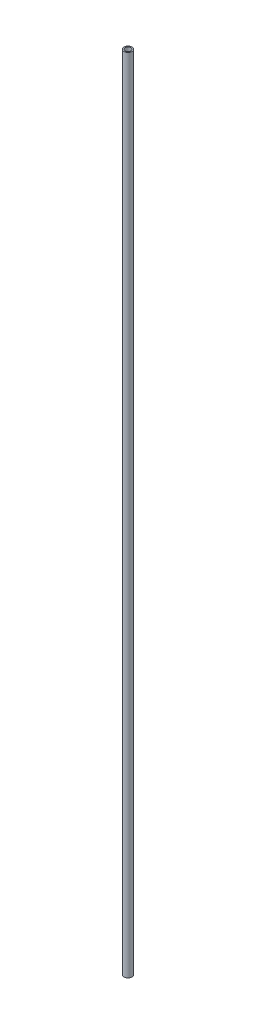
SolidWorks part; units mm, degrees
ref_plane "Front Plane" through (0, 0, 0) normal (0, 0, 1) x (1, 0, 0)
ref_plane "Top Plane" through (0, 0, 0) normal (0, 1, 0) x (1, 0, 0)
ref_plane "Right Plane" through (0, 0, 0) normal (1, 0, 0) x (0, 0, -1)
sketch "Sketch1" plane through (0, 0, 0) normal (0, 1, 0) x (1, 0, 0)
  circle A0 centre (0, 0) radius 9.5
  circle A1 centre (0, 0) radius 6.9
  dimension "D1" = 19
  dimension "D2" = 2.6
extrude "Boss-Extrude1" add sketch "Sketch1" along normal blind 1930
equation "\"indoorHeight\"=1940.0"
equation "\"D1@Boss-Extrude1\"=\"indoorHeight\"+20-90+30+70-20-20"
equation "\"CarBeamWidth\"=700.0"
equation "\"WheelWidth\"=650.0"
equation "\"Wheel_FrontBoxDistance\"=1390.0"
equation "\"MetalSheet_3mm_length\"=5030.0"
equation "\"MetalSheet_3mm_width\"=1923.0"
equation "\"MetalSheet_3mm_FloorCut_L_length\"=1764.0"
equation "\"MetalSheet_3mm_FloorCut_L_disdance\"=1665.0"
equation "\"MetalSheet_3mm_FloorCut_R_length\"=1764.0"
equation "\"MetalSheet_3mm_FloorCut_R_disdance\"=1665.0"
equation "\"haveDoor_R\"=1"
equation "\"side_door_bottom_R_3mm_length\"=1934.0"
equation "\"1Bar_Side_RF_3mm_length\"=1493.0"
equation "\"1Bar_Side_RB_3mm_length\"=1493.0"
equation "\"DoorSeparator_RF_3mm_withHinge_toFrontDistance\"=1673.0"
equation "\"DoorSeparator_RF_3mm_withHinge_exist\"=1"
equation "\"DoorSeparator_RB_3mm_withHinge_toFrontDistance\"=3427.0"
equation "\"DoorSeparator_RB_3mm_withHinge_exist\"=1"
equation "\"Door_R1_L_open_Single_toFrontDistance\"=2547.5"
equation "\"Door_R1_L_open_Single_exist\"=1"
equation "\"door_base_long7_R1_L_open_Single_height\"=1890.0"
equation "\"door_base_short7_R1_L_open_Single_height\"=1890.0"
equation "\"door_base_short7_R1_L_open_Single_width\"=864"
equation "\"Door_R1_R_open_Single_toFrontDistance\"=3422.0"
equation "\"Door_R1_R_open_Single_exist\"=1"
equation "\"door_base_long7_R1_R_open_Single_height\"=1890.0"
equation "\"door_base_short7_R1_R_open_Single_height\"=1890.0"
equation "\"door_base_short7_R1_R_open_Single_width\"=864"
equation "\"x\"=66.0"
equation "\"da\"=62.0"
equation "\"SquareTube_length\"=1923.0"
equation "\"channelSteel_length\"=5030.0"
equation "\"SquareTube_inFront_AvgDistance\"=285.0"
equation "\"SquareTube_inFront_TotalCount\"=5"
equation "\"SquareTube_inFront1_cutDepth50_R\"=0.5"
equation "\"SquareTube_inFront1_cutDepth50_L\"=0.5"
equation "\"SquareTube_inFront2_cutDepth50_R\"=0.5"
equation "\"SquareTube_inFront2_cutDepth50_L\"=0.5"
equation "\"SquareTube_inFront3_cutDepth50_R\"=0.5"
equation "\"SquareTube_inFront3_cutDepth50_L\"=0.5"
equation "\"SquareTube_inFront4_cutDepth50_R\"=0.5"
equation "\"SquareTube_inFront4_cutDepth50_L\"=0.5"
equation "\"SquareTube_inFront5_cutDepth50_R\"=50"
equation "\"SquareTube_inFront5_cutDepth50_L\"=50"
equation "\"SquareTube_inFront6_cutDepth50_R\"=50"
equation "\"SquareTube_inFront6_cutDepth50_L\"=50"
equation "\"SquareTube_inFront7_cutDepth50_R\"=50"
equation "\"SquareTube_inFront7_cutDepth50_L\"=50"
equation "\"SquareTube_inFront8_cutDepth50_R\"=50"
equation "\"SquareTube_inFront8_cutDepth50_L\"=50"
equation "\"SquareTube_inFront9_cutDepth50_R\"=50"
equation "\"SquareTube_inFront9_cutDepth50_L\"=50"
equation "\"SquareTube_inFront10_cutDepth50_R\"=50"
equation "\"SquareTube_inFront10_cutDepth50_L\"=50"
equation "\"SquareTube_inFront11_cutDepth50_R\"=50"
equation "\"SquareTube_inFront11_cutDepth50_L\"=50"
equation "\"SquareTube_inFront12_cutDepth50_R\"=50"
equation "\"SquareTube_inFront12_cutDepth50_L\"=50"
equation "\"SquareTube_inFront13_cutDepth50_R\"=50"
equation "\"SquareTube_inFront13_cutDepth50_L\"=50"
equation "\"SquareTube_inFront14_cutDepth50_R\"=50"
equation "\"SquareTube_inFront14_cutDepth50_L\"=50"
equation "\"SquareTube_inBack_AvgDistance\"=333.125"
equation "\"SquareTube_inBack_TotalCount\"=9"
equation "\"SquareTube_inBack1_cutDepth50_R\"=50"
equation "\"SquareTube_inBack1_cutDepth50_L\"=50"
equation "\"SquareTube_inBack2_cutDepth50_R\"=50"
equation "\"SquareTube_inBack2_cutDepth50_L\"=50"
equation "\"SquareTube_inBack3_cutDepth50_R\"=50"
equation "\"SquareTube_inBack3_cutDepth50_L\"=50"
equation "\"SquareTube_inBack4_cutDepth50_R\"=50"
equation "\"SquareTube_inBack4_cutDepth50_L\"=50"
equation "\"SquareTube_inBack5_cutDepth50_R\"=50"
equation "\"SquareTube_inBack5_cutDepth50_L\"=50"
equation "\"SquareTube_inBack6_cutDepth50_R\"=0.5"
equation "\"SquareTube_inBack6_cutDepth50_L\"=0.5"
equation "\"SquareTube_inBack7_cutDepth50_R\"=0.5"
equation "\"SquareTube_inBack7_cutDepth50_L\"=0.5"
equation "\"SquareTube_inBack8_cutDepth50_R\"=0.5"
equation "\"SquareTube_inBack8_cutDepth50_L\"=0.5"
equation "\"indoorHeight_para\"=25.0"
equation "\"side_door_bottom_R_3mm_toFrontDistance\"=1583.0"
